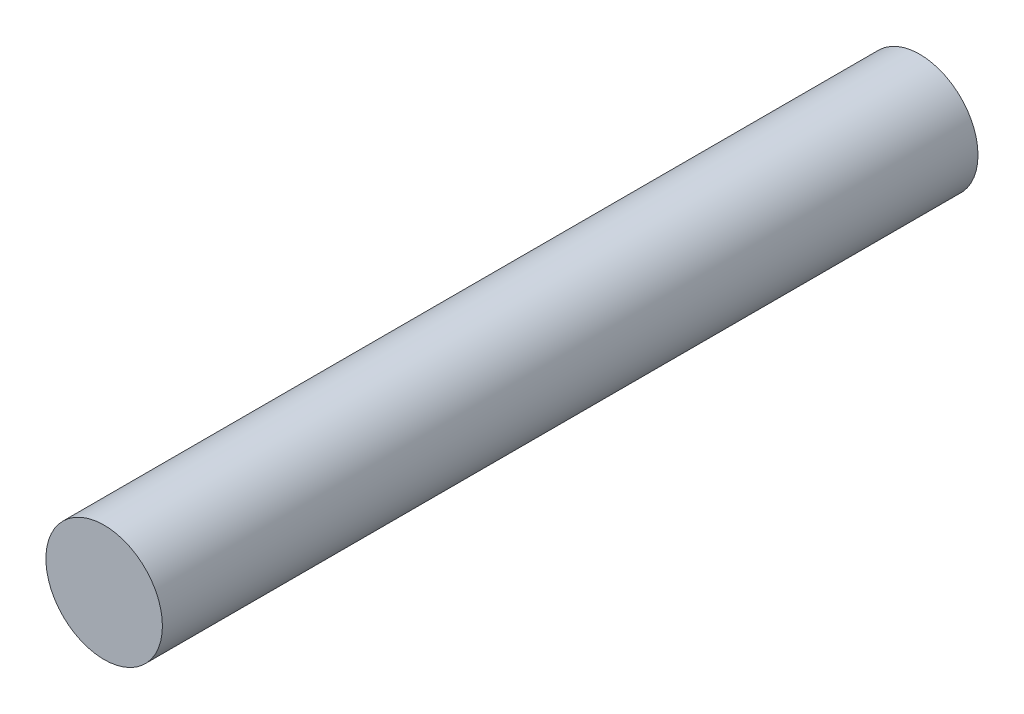
SolidWorks part; units mm, degrees
ref_plane "Front Plane" through (0, 0, 0) normal (0, 0, 1) x (1, 0, 0)
ref_plane "Top Plane" through (0, 0, 0) normal (0, 1, 0) x (1, 0, 0)
ref_plane "Right Plane" through (0, 0, 0) normal (1, 0, 0) x (0, 0, -1)
sketch "Sketch1" plane through (0, 0, 0) normal (0, 0, 1) x (1, 0, 0)
  circle A0 centre (0, 0) radius 3.175
  dimension "D1" = 6.35
extrude "Boss-Extrude1" add sketch "Sketch1" along normal blind 44.45
